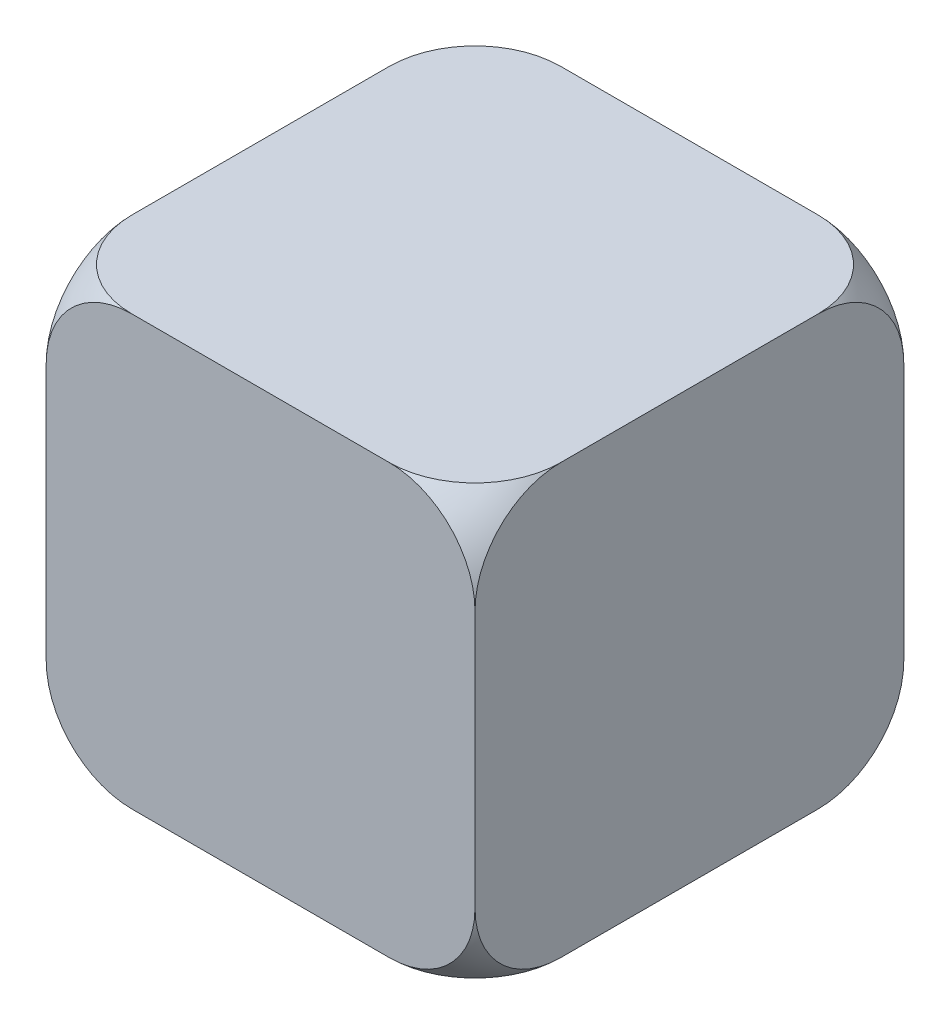
SolidWorks part; units mm, degrees
ref_plane "Plano frontal" through (0, 0, 0) normal (0, 0, 1) x (1, 0, 0)
ref_plane "Plano superior" through (0, 0, 0) normal (0, 1, 0) x (1, 0, 0)
ref_plane "Plano direito" through (0, 0, 0) normal (1, 0, 0) x (0, 0, -1)
sketch3d "3DSketch1"
  line L0 (0, 0, 0) -> (2, 0, 0) construction
  line L1 (2, 0, 0) -> (8, 0, 0) construction
  line L2 (8, 0, 0) -> (10, 0, 0) construction
  line L3 (0, 0, 0) -> (0, 0, 2) construction
  line L4 (0, 0, 2) -> (0, 0, 8) construction
  line L5 (0, 0, 8) -> (0, 0, 10) construction
  line L6 (10, 0, 0) -> (10, 0, 2) construction
  line L7 (0, 0, 10) -> (2, 0, 10) construction
  line L8 (10, 0, 2) -> (10, 0, 8) construction
  line L9 (2, 0, 10) -> (8, 0, 10) construction
  line L10 (10, 0, 8) -> (10, 0, 10) construction
  line L11 (8, 0, 10) -> (10, 0, 10) construction
  line L12 (0, 0, 8) -> (2, 0, 8) construction
  line L13 (2, 0, 10) -> (2, 0, 8) construction
  line L14 (10, 0, 8) -> (8, 0, 8) construction
  line L15 (8, 0, 10) -> (8, 0, 8) construction
  line L16 (2, 0, 8) -> (2, 2, 8) construction
  line L17 (8, 0, 8) -> (8, 2, 8) construction
  line L18 (2, 2, 8) -> (2, 8, 8) construction
  line L19 (8, 2, 8) -> (8, 8, 8) construction
  line L20 (2, 8, 8) -> (2, 10, 8) construction
  line L21 (8, 8, 8) -> (8, 10, 8) construction
  line L22 (0, 0, 2) -> (2, 0, 2) construction
  line L23 (2, 0, 2) -> (2, 2, 2) construction
  line L24 (2, 0, 0) -> (2, 0, 2) construction
  line L25 (2, 2, 2) -> (2, 8, 2) construction
  line L26 (10, 0, 2) -> (8, 0, 2) construction
  line L27 (2, 8, 2) -> (2, 10, 2) construction
  line L28 (8, 0, 0) -> (8, 0, 2) construction
  line L29 (8, 0, 2) -> (8, 2, 2) construction
  line L30 (8, 2, 2) -> (8, 8, 2) construction
  line L31 (8, 8, 2) -> (8, 10, 2) construction
  line L32 (2, 0, 2) -> (4, 0, 2) construction
  line L33 (8, 0, 2) -> (6, 0, 2) construction
  line L34 (2, 2, 2) -> (-0.8284, 2, 2)
  line L35 (2, 2, 2) -> (4.8284, 2, 2)
  line L36 (8, 2, 2) -> (5.1716, 2, 2)
  line L37 (8, 2, 2) -> (10.8284, 2, 2)
  arc A0 (-0.8284, 2, 2) -> (4.8284, 2, 2) centre (2, 2, 2) ccw
  arc A1 (5.1716, 2, 2) -> (10.8284, 2, 2) centre (8, 2, 2) ccw
  point P32 (2, 2, 4.8284)
  point P34 (8, 2, 4.8284)
  dimension "D1" = 2
  dimension "D2" = 2
  dimension "D3" = 10
  dimension "D4" = 2
  dimension "D5" = 2
  dimension "D6" = 10
  dimension "D7" = 2
  dimension "D8" = 2
  dimension "D9" = 2
  dimension "D10" = 2
  dimension "D11" = 2
  dimension "D12" = 2
  dimension "D13" = 2
  dimension "D14" = 2
  dimension "D15" = 10
  dimension "D16" = 10
  dimension "D17" = 2
  dimension "D18" = 2
  dimension "D19" = 10
  dimension "D20" = 2
  dimension "D21" = 2
  dimension "D22" = 10
  dimension "D23" = 2
  dimension "D24" = 2
ref_plane "Plano1" through (0, 0, 2) normal (0, 0, 1) x (1, 0, 0)
sketch "Esboço2" plane through (0, 0, 2) normal (0, 0, 1) x (1, 0, 0)
  line L0 (2, 2) -> (-0.8284, 2) construction
  line L1 (2, 2) -> (4.8284, 2) construction
  line L2 (2, 2) -> (-0.8284, 2)
  line L3 (2, 2) -> (4.8284, 2)
  line L4 (8, 2) -> (5.1716, 2) construction
  line L5 (8, 2) -> (10.8284, 2) construction
  line L6 (8, 2) -> (5.1716, 2)
  line L7 (8, 2) -> (10.8284, 2)
  arc A0 (-0.8284, 2) -> (4.8284, 2) centre (2, 2) ccw construction
  arc A1 (-0.8284, 2) -> (4.8284, 2) centre (2, 2) ccw
  arc A2 (5.1716, 2) -> (10.8284, 2) centre (8, 2) ccw construction
  arc A3 (5.1716, 2) -> (10.8284, 2) centre (8, 2) ccw
revolve "Revolução1" add sketch "Esboço2" angle 360 about L2
pattern_linear "Padrão linear2" count 2 spacing 6 along (0, 0, 1) count 2 spacing 6 along (0, 1, 0) of bodies 102 101
sketch "Esboço3" plane through (0, 0, 0) normal (0, 0, 1) x (1, 0, 0)
  line L0 (2, 8) -> (2, 10)
  line L1 (0, 0) -> (2, 0)
  line L2 (0, 0) -> (0, 2)
  line L3 (0, 10) -> (2, 10)
  line L4 (10, 0) -> (10, 2)
  line L5 (-5, -5) -> (15, -5)
  line L6 (-5, -5) -> (-5, 15)
  line L7 (-5, 15) -> (15, 15)
  line L8 (15, -5) -> (15, 15)
  line L9 (2, 8) -> (0, 8)
  line L10 (2, 2) -> (2, 0)
  line L11 (2, 2) -> (0, 2)
  line L12 (8, 2) -> (8, 0)
  line L13 (8, 2) -> (10, 2)
  line L14 (8, 8) -> (10, 8)
  line L15 (8, 8) -> (8, 10)
  line L16 (10, 8) -> (10, 10)
  line L17 (0, 8) -> (0, 10)
  line L18 (8, 0) -> (10, 0)
  line L19 (8, 10) -> (10, 10)
  circle A0 centre (8, 8) radius 2.8284 construction
  circle A1 centre (2, 8) radius 2.8284 construction
  circle A2 centre (2, 2) radius 2.8284 construction
  circle A3 centre (8, 2) radius 2.8284 construction
  circle A4 centre (8, 8) radius 2.8284 construction
  circle A5 centre (2, 8) radius 2.8284 construction
  circle A6 centre (2, 2) radius 2.8284 construction
  circle A7 centre (8, 2) radius 2.8284 construction
  dimension "D1" = 10
  dimension "D2" = 5
  dimension "D3" = 5
  dimension "D4" = 5
  dimension "D5" = 5
  dimension "D6" = 10
extrude "Corte-extrusão1" cut sketch "Esboço3" against normal through all and the other way through all
sketch "Esboço4" plane through (0, 0, 0) normal (1, 0, 0) x (0, 0, -1)
  line L0 (-8, 8) -> (-10, 8)
  line L1 (0, 0) -> (-2, 0)
  line L2 (0, 0) -> (0, 2)
  line L3 (0, 10) -> (-2, 10)
  line L4 (-10, 0) -> (-10, 2)
  line L5 (-15, 15) -> (5, 15)
  line L6 (-15, 15) -> (-15, -5)
  line L7 (-15, -5) -> (5, -5)
  line L8 (5, 15) -> (5, -5)
  line L9 (-6, 8) -> (-10, 8) construction
  line L10 (-8, 8) -> (-8, 10)
  line L11 (-8, 2) -> (-8, 0)
  line L12 (-6, 2) -> (-10, 2) construction
  line L13 (-8, 2) -> (-10, 2)
  line L14 (-2, 2) -> (-2, 0)
  line L15 (0, 2) -> (-4, 2) construction
  line L16 (-2, 2) -> (0, 2)
  line L17 (-2, 8) -> (0, 8)
  line L18 (0, 8) -> (-4, 8) construction
  line L19 (-2, 8) -> (-2, 10)
  line L20 (-10, 8) -> (-10, 10)
  line L21 (0, 8) -> (0, 10)
  line L22 (-8, 0) -> (-10, 0)
  line L23 (-8, 10) -> (-10, 10)
  dimension "D2" = 5
  dimension "D3" = 5
  dimension "D4" = 5
  dimension "D5" = 5
extrude "Corte-extrusão3" cut sketch "Esboço4" against normal blind 10 and the other way blind 20
sketch "Esboço5" plane through (0, 0, 2) normal (0, 0, 1) x (1, 0, 0)
  line L1 (10, 10) -> (0, 10)
  line L2 (10, 10) -> (10, 0)
  line L3 (10, 0) -> (0, 0)
  line L4 (0, 10) -> (0, 0)
extrude "Ressalto-extrusão1" add sketch "Esboço5" along normal up to vertex (6 mm away) up to point (8, 8, 8)
sketch "Esboço6" plane through (2, 0, 0) normal (1, 0, 0) x (0, 0, -1)
  line L1 (-10, 10) -> (0, 10)
  line L2 (-10, 10) -> (-10, 0)
  line L3 (-10, 0) -> (0, 0)
  line L4 (0, 10) -> (0, 0)
extrude "Ressalto-extrusão2" add sketch "Esboço6" along normal up to vertex (6 mm away) up to point (8, 8, 8)
sketch "Esboço7" plane through (0, 2, 0) normal (0, 1, 0) x (1, 0, 0)
  line L1 (10, -10) -> (0, -10)
  line L2 (10, -10) -> (10, 0)
  line L3 (10, 0) -> (0, 0)
  line L4 (0, -10) -> (0, 0)
extrude "Ressalto-extrusão3" add sketch "Esboço7" along normal up to vertex (6 mm away) up to point (8, 8, 8)
